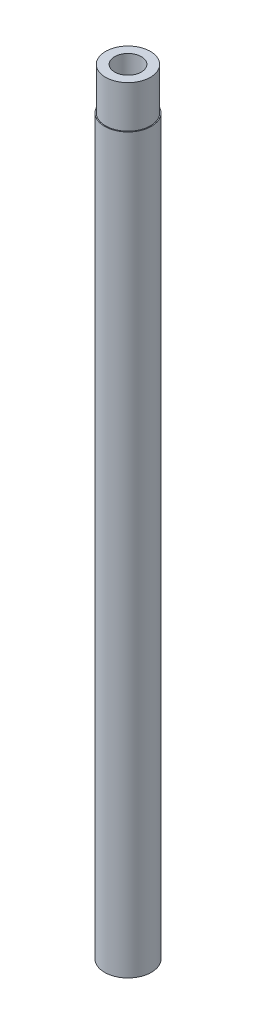
SolidWorks part; units mm, degrees
ref_plane "Front Plane" through (0, 0, 0) normal (0, 0, 1) x (1, 0, 0)
ref_plane "Top Plane" through (0, 0, 0) normal (0, 1, 0) x (1, 0, 0)
ref_plane "Right Plane" through (0, 0, 0) normal (1, 0, 0) x (0, 0, -1)
sketch "Sketch1" plane through (0, 0, 0) normal (0, 1, 0) x (1, 0, 0)
  circle A0 centre (0, 0) radius 11.1125
  circle A1 centre (0, 0) radius 6.35
  dimension "D1" = 12.7
  dimension "D2" = 22.225
extrude "Boss-Extrude1" add sketch "Sketch1" along normal blind 368.3
sketch "Sketch2" plane through (0, 368.3, 0) normal (0, 1, 0) x (1, 0, 0)
  circle A0 centre (0, 0) radius 10.668
  circle A1 centre (0, 0) radius 11.1125 construction
  circle A2 centre (0, 0) radius 11.1125
  dimension "D1" = 21.336
extrude "Cut-Extrude1" cut sketch "Sketch2" against normal blind 20
sketch "Sketch3" plane through (0, 0, 0) normal (0, -1, 0) x (1, 0, 0)
  circle A0 centre (0, 0) radius 7.1438
  circle A1 centre (0, 0) radius 6.35 construction
  circle A2 centre (0, 0) radius 6.35
  dimension "D1" = 14.2875
extrude "Cut-Extrude2" cut sketch "Sketch3" against normal blind 12.7
